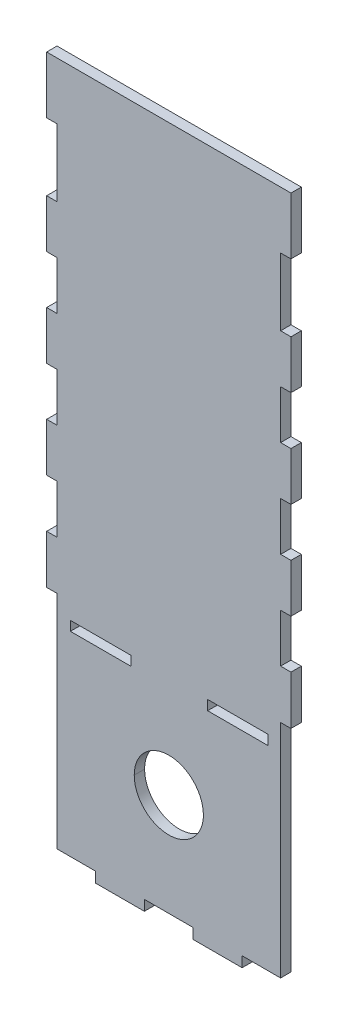
SolidWorks part; units mm, degrees
ref_plane "Front Plane" through (0, 0, 0) normal (0, 0, 1) x (1, 0, 0)
ref_plane "Top Plane" through (0, 0, 0) normal (0, 1, 0) x (1, 0, 0)
ref_plane "Right Plane" through (0, 0, 0) normal (1, 0, 0) x (0, 0, -1)
sketch "Model" plane through (0, 0, 0) normal (0, 0, 1) x (1, 0, 0)
  line L0 (1149.5543, -552.5806) -> (1145.0543, -552.5806)
  line L1 (1145.0543, -552.5806) -> (1145.0543, -527.8307)
  line L2 (1145.0543, -527.8307) -> (1166.2544, -527.8307)
  line L3 (1149.5543, -707.9111) -> (1149.5543, -686.8304)
  line L4 (1149.5543, -686.8304) -> (1145.0543, -686.8304)
  line L5 (1145.0543, -686.8304) -> (1145.0543, -665.8305)
  line L6 (1145.0543, -665.8305) -> (1149.5543, -665.8305)
  line L7 (1149.5543, -665.8305) -> (1149.5543, -644.8306)
  line L8 (1149.5543, -644.8306) -> (1145.0543, -644.8306)
  line L9 (1145.0543, -644.8306) -> (1145.0543, -623.8307)
  line L10 (1145.0543, -623.8307) -> (1149.5543, -623.8307)
  line L11 (1149.5543, -623.8307) -> (1149.5543, -602.8307)
  line L12 (1149.5543, -602.8307) -> (1145.0543, -602.8307)
  line L13 (1145.0543, -602.8307) -> (1145.0543, -581.8305)
  line L14 (1145.0543, -581.8305) -> (1149.5543, -581.8305)
  line L15 (1246.5544, -581.8305) -> (1251.0544, -581.8305)
  line L16 (1251.0544, -581.8305) -> (1251.0544, -602.8307)
  line L17 (1251.0544, -602.8307) -> (1246.5544, -602.8307)
  line L18 (1246.5544, -602.8307) -> (1246.5544, -623.8307)
  line L19 (1246.5544, -623.8307) -> (1251.0544, -623.8307)
  line L20 (1251.0544, -623.8307) -> (1251.0544, -644.8306)
  line L21 (1251.0544, -644.8306) -> (1246.5544, -644.8306)
  line L22 (1246.5544, -644.8306) -> (1246.5544, -665.8305)
  line L23 (1246.5544, -665.8305) -> (1251.0544, -665.8305)
  line L24 (1251.0544, -665.8305) -> (1251.0544, -686.8304)
  line L25 (1251.0544, -686.8304) -> (1246.5544, -686.8304)
  line L26 (1246.5544, -686.8304) -> (1246.5544, -707.8307)
  line L27 (1246.5544, -707.8307) -> (1251.0544, -707.8307)
  line L28 (1229.8543, -527.8307) -> (1251.0544, -527.8307)
  line L29 (1251.0544, -527.8307) -> (1251.0544, -552.5806)
  line L30 (1251.0544, -552.5806) -> (1246.5544, -552.5806)
  line L31 (1149.5543, -707.9111) -> (1145.0543, -707.9111)
  line L32 (1145.0543, -707.9111) -> (1145.0543, -729.0027)
  line L33 (1145.0543, -729.0027) -> (1149.5543, -729.0027)
  line L34 (1246.5544, -729.0027) -> (1251.0544, -729.0027)
  line L35 (1251.0544, -729.0027) -> (1251.0544, -707.8307)
  line L36 (1149.5543, -729.0027) -> (1149.5543, -825.0027)
  line L37 (1246.5544, -729.0027) -> (1246.5544, -825.0027)
  line L38 (1196.5044, -825.0027) -> (1187.4541, -825.0027)
  line L39 (1187.4541, -825.0027) -> (1187.4541, -829.5027)
  line L40 (1187.4541, -829.5027) -> (1166.2544, -829.5027)
  line L41 (1166.2544, -829.5027) -> (1166.2544, -825.0027)
  line L42 (1166.2544, -825.0027) -> (1149.5543, -825.0027)
  line L43 (1246.5544, -825.0027) -> (1229.8543, -825.0027)
  line L44 (1229.8543, -825.0027) -> (1229.8543, -829.5027)
  line L45 (1229.8543, -829.5027) -> (1208.6546, -829.5027)
  line L46 (1208.6546, -829.5027) -> (1208.6546, -825.0027)
  line L47 (1208.6546, -825.0027) -> (1199.6043, -825.0027)
  line L48 (1196.5044, -825.0027) -> (1199.6043, -825.0027)
  line L49 (1241.0722, -740.4089) -> (1214.9019, -740.4089)
  line L50 (1214.9019, -740.4089) -> (1214.9019, -736.1666)
  line L51 (1214.9019, -736.1666) -> (1241.0722, -736.1666)
  line L52 (1241.0722, -736.1666) -> (1241.0722, -740.4089)
  line L53 (1155.3472, -740.3476) -> (1181.5592, -740.3476)
  line L54 (1181.5592, -740.3476) -> (1181.5592, -736.2279)
  line L55 (1181.5592, -736.2279) -> (1155.3472, -736.2279)
  line L56 (1155.3472, -736.2279) -> (1155.3472, -740.3476)
  line L57 (1149.5543, -552.5806) -> (1149.5543, -581.8305)
  line L58 (1246.5544, -552.5806) -> (1246.5544, -581.8305)
  spline S0 degree 2 poles (1229.8543, -527.8307) (1215.6171, -527.8307) (1198.0544, -527.8307) knots 0 0 0 1 1 1
  spline S1 degree 2 poles (1198.0544, -527.8307) (1180.4916, -527.8307) (1166.2544, -527.8307) knots 1 1 1 2 2 2
  spline S2 degree 3 poles (1183.0544, -780.5236) (1183.0544, -772.2393) (1189.7703, -765.5237) (1198.0544, -765.5237) (1206.3384, -765.5237) (1213.0543, -772.2393) (1213.0543, -780.5236) knots 2 2 2 2 3 3 3 4 4 4 4
  spline S3 degree 3 poles (1213.0543, -780.5236) (1213.0543, -788.8078) (1206.3384, -795.5235) (1198.0544, -795.5235) (1189.7703, -795.5235) (1183.0544, -788.8078) (1183.0544, -780.5236) knots 0 0 0 0 1 1 1 2 2 2 2
extrude "Boss-Extrude1" add sketch "Model" along normal blind 4.5
